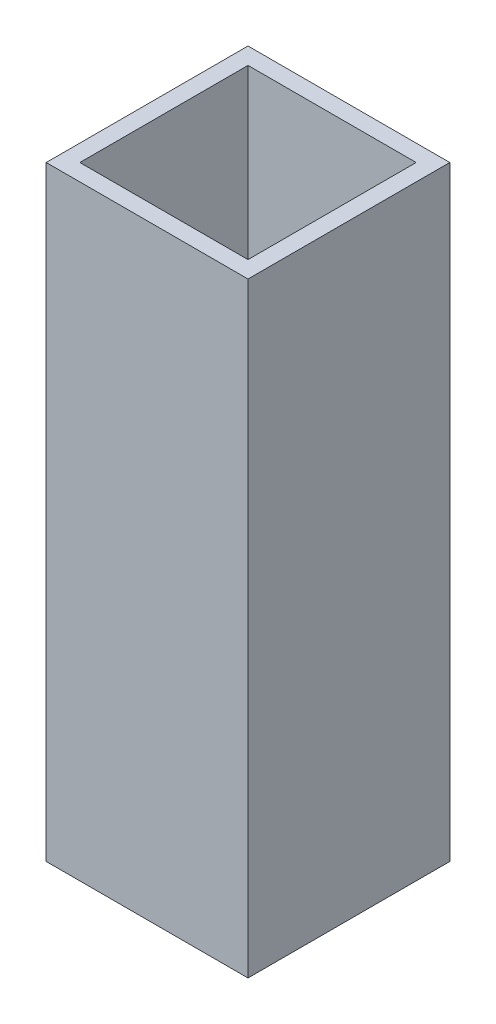
SolidWorks part; units mm, degrees
ref_plane "Front Plane" through (0, 0, 0) normal (0, 0, 1) x (1, 0, 0)
ref_plane "Top Plane" through (0, 0, 0) normal (0, 1, 0) x (1, 0, 0)
ref_plane "Right Plane" through (0, 0, 0) normal (1, 0, 0) x (0, 0, -1)
sketch "Sketch1" plane through (0, 0, 0) normal (1, 0, 0) x (0, 0, -1)
  line L1 (0, 0) -> (76.2, 0)
  line L2 (0, 0) -> (0, 228.6)
  line L3 (0, 228.6) -> (76.2, 228.6)
  line L4 (76.2, 0) -> (76.2, 228.6)
  dimension "D1" = 76.2
  dimension "D2" = 228.6
extrude "Boss-Extrude1" add sketch "Sketch1" along normal blind 76.2
shell "Shell1" thickness 6.35
